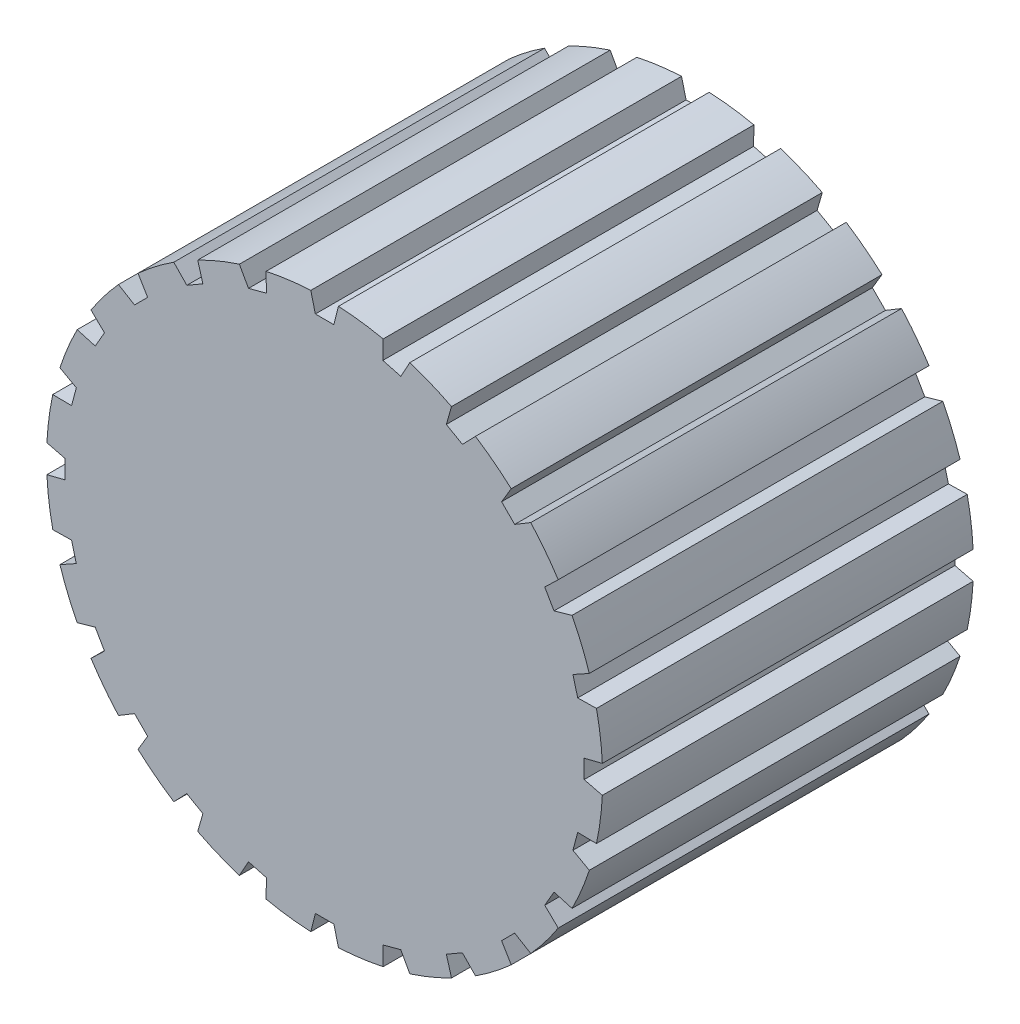
SolidWorks part; units mm, degrees
ref_plane "Front Plane" through (0, 0, 0) normal (0, 0, 1) x (1, 0, 0)
ref_plane "Top Plane" through (0, 0, 0) normal (0, 1, 0) x (1, 0, 0)
ref_plane "Right Plane" through (0, 0, 0) normal (1, 0, 0) x (0, 0, -1)
other "Configuration Table"
sketch "草图1" plane through (0, 0, 0) normal (0, 0, 1) x (1, 0, 0)
  circle A0 centre (0, 0) radius 1.5
  dimension "D1" = 3
extrude "凸台-拉伸1" add sketch "草图1" along normal mid plane 2
sketch "草图2" plane through (0, 0, 1) normal (0, 0, 1) x (1, 0, 0)
  line L0 (-0.075, 1.5) -> (-0.05, 1.4)
  line L1 (-0.05, 1.4) -> (0.05, 1.4)
  line L2 (0.05, 1.4) -> (0.075, 1.5)
  line L3 (0.075, 1.5) -> (-0.075, 1.5)
  line L4 (0, 1.5) -> (0, 1.4) construction
  circle A0 centre (0, 0) radius 1.5 construction
  dimension "D1" = 0.15
  dimension "D2" = 0.1
  dimension "D3" = 0.1
extrude "切除-拉伸1" cut sketch "草图2" against normal blind 4
pattern_circular "阵列(圆周)1" count 24 over 360 about axis through (0, 0, 0) along (0, 0, 1) of "切除-拉伸1"
